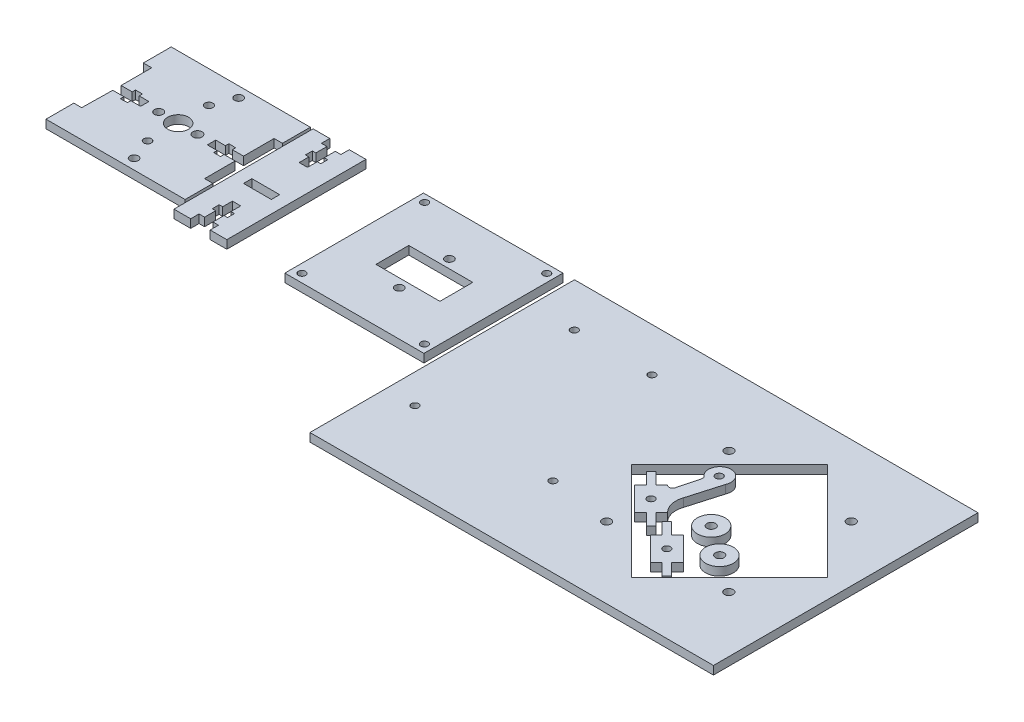
SolidWorks part; units mm, degrees
ref_plane "Front Plane" through (0, 0, 0) normal (0, 0, 1) x (1, 0, 0)
ref_plane "Top Plane" through (0, 0, 0) normal (0, 1, 0) x (1, 0, 0)
ref_plane "Right Plane" through (0, 0, 0) normal (1, 0, 0) x (0, 0, -1)
other "Graphic1"
other "Graphic (Closed) -1"
other "Graphic (Closed) -2"
other "Graphic (Closed) -3"
other "Graphic (Closed) -4"
other "Graphic (Closed) -5"
other "Graphic (Closed) -6"
other "Graphic (Closed) -7"
other "Graphic (Closed) -8"
other "Graphic (Closed) -9"
other "Graphic (Closed) -10"
other "Graphic (Closed) -11"
other "Graphic (Closed) -12"
other "Graphic (Closed) -13"
other "Graphic (Closed) -14"
other "Graphic (Closed) -15"
other "Graphic (Closed) -16"
other "Graphic (Closed) -17"
other "Graphic (Closed) -18"
other "Graphic (Closed) -19"
other "Graphic (Closed) -20"
other "Graphic (Closed) -21"
other "Graphic (Closed) -22"
other "Graphic (Closed) -23"
other "Graphic (Closed) -24"
other "Graphic (Closed) -25"
other "Graphic (Closed) -26"
other "Graphic (Closed) -27"
other "Graphic (Closed) -28"
other "Graphic (Closed) -29"
other "Graphic (Closed) -30"
other "Graphic (Closed) -31"
other "Graphic (Closed) -32"
other "Graphic (Closed) -33"
other "Graphic (Closed) -34"
other "Graphic (Closed) -35"
other "Graphic (Closed) -36"
other "Graphic (Closed) -37"
sketch "Sketch3" plane through (0, 0, 0) normal (0, 1, 0) x (1, 0, 0)
  line L0 (0, 0) -> (50, 0)
  line L1 (50, 0) -> (50, -10)
  line L2 (50, -10) -> (47, -10)
  line L3 (47, -10) -> (47, -21)
  line L4 (47, -21) -> (43, -21)
  line L5 (43, -21) -> (43, -19.8259)
  line L6 (43, -19.8259) -> (40.5, -19.75)
  line L7 (40.5, -19.75) -> (40.5, -21)
  line L8 (40.5, -21) -> (37, -21)
  line L9 (37, -21) -> (37, -24)
  line L10 (37, -24) -> (40.5, -24)
  line L11 (40.5, -24) -> (40.5, -25.275)
  line L12 (40.5, -25.275) -> (43, -25.25)
  line L13 (43, -25.25) -> (43, -24)
  line L14 (43, -24) -> (47, -24)
  line L15 (47, -24) -> (47, -35)
  line L16 (47, -35) -> (50, -35)
  line L17 (50, -35) -> (50, -45)
  line L18 (50, -45) -> (0, -45)
  line L19 (0, -45) -> (0, -35)
  line L20 (0, -35) -> (2.8271, -35)
  line L21 (3, -24) -> (7, -24)
  line L22 (7, -24) -> (7, -25.275)
  line L23 (7, -25.275) -> (9.5, -25.1741)
  line L24 (9.5, -25.1741) -> (9.5, -24)
  line L25 (9.5, -24) -> (13, -24)
  line L26 (13, -24) -> (13, -21)
  line L27 (13, -21) -> (9.5, -21)
  line L28 (9.5, -21) -> (9.5, -19.8259)
  line L29 (9.5, -19.8259) -> (7, -19.8259)
  line L30 (7, -19.8259) -> (7, -21)
  line L31 (7, -21) -> (3, -21)
  line L32 (3, -21) -> (3, -10)
  line L33 (3, -10) -> (0, -10)
  line L34 (0, -10) -> (0, 0)
  line L35 (2.8271, -35) -> (3, -24)
  circle A0 centre (25, -22.5) radius 3.75
  circle A1 centre (18, -22.5) radius 1.5333
  circle A2 centre (24.9904, -11.4176) radius 1.4239
  circle A3 centre (31.9506, -22.5119) radius 1.6482
  circle A4 centre (28, -3.75) radius 1.5
  circle A5 centre (25, -33.4941) radius 1.3524
  circle A6 centre (27.9864, -41.3394) radius 1.4891
  dimension "D1" = 10
extrude "Boss-Extrude1" add sketch "Sketch3" along normal blind 3
sketch "Sketch5" plane through (0, 0, 0) normal (0, 1, 0) x (1, 0, 0)
  line L0 (57, 0) -> (57, -3)
  line L1 (57, -3) -> (59, -3)
  line L2 (59, -3) -> (59, -7)
  line L3 (59, -7) -> (57.75, -7)
  line L4 (57.75, -7) -> (57.75, -9.5)
  line L5 (57.75, -9.5) -> (59, -9.5)
  line L6 (59, -9.5) -> (59, -13)
  line L7 (59, -13) -> (62, -13)
  line L8 (62, -13) -> (62, -9.5)
  line L9 (62, -9.5) -> (63.25, -9.5)
  line L10 (63.25, -9.5) -> (63.25, -7)
  line L11 (63.25, -7) -> (62, -7)
  line L12 (62, -7) -> (62, -3)
  line L13 (62, -3) -> (64, -3)
  line L14 (64, -3) -> (64, 0)
  line L15 (64, 0) -> (70, 0)
  line L16 (70, 0) -> (70, -50)
  line L17 (70, -50) -> (64, -50)
  line L18 (64, -50) -> (64, -47)
  line L19 (64, -47) -> (62, -47)
  line L20 (62, -47) -> (62, -43)
  line L21 (62, -43) -> (63.25, -43)
  line L22 (63.25, -43) -> (63.25, -40.5)
  line L23 (63.25, -40.5) -> (62, -40.5)
  line L24 (62, -40.5) -> (62, -37)
  line L25 (62, -37) -> (59, -37)
  line L26 (59, -37) -> (59, -40.5)
  line L27 (59, -40.5) -> (57.75, -40.5)
  line L28 (57.75, -40.5) -> (57.75, -43)
  line L29 (57.75, -43) -> (59, -43)
  line L30 (59, -43) -> (59, -47)
  line L31 (59, -47) -> (57, -47)
  line L32 (57, -47) -> (57, -50)
  line L33 (57, -50) -> (51, -50)
  line L34 (51, -50) -> (51, 0)
  line L35 (51, 0) -> (57, 0)
  line L36 (55.5, -26.5) -> (65.5, -26.5)
  line L37 (65.5, -26.5) -> (65.5, -29.5)
  line L38 (65.5, -29.5) -> (55.5, -29.5)
  line L39 (55.5, -29.5) -> (55.5, -26.5)
extrude "Boss-Extrude2" add sketch "Sketch5" along normal blind 3 separate body
sketch "Sketch8" plane through (0, 0, 0) normal (0, 1, 0) x (1, 0, 0)
  line L0 (104.5, -19.1) -> (127.5, -19.1)
  line L1 (127.5, -19.1) -> (127.5, -30.9)
  line L2 (127.5, -30.9) -> (104.5, -30.9)
  line L3 (104.5, -30.9) -> (104.5, -19.1)
  line L4 (90.8358, -0.1468) -> (90.8358, -49.9799)
  line L5 (90.8358, -49.9799) -> (140.8298, -49.9799)
  line L6 (140.8298, -49.9799) -> (140.8298, 0)
  line L7 (140.8298, 0) -> (90.8358, -0.1468)
  circle A0 centre (116, -16) radius 1.5
  circle A1 centre (116, -34) radius 1.5
  circle A2 centre (138, -3) radius 1.3
  circle A3 centre (94, -47) radius 1.3
  circle A4 centre (93.9724, -2.8702) radius 1.295
  circle A5 centre (138, -47) radius 1.3
extrude "Boss-Extrude3" add sketch "Sketch8" along normal blind 3 separate body
sketch "Sketch14" plane through (0, 0, 0) normal (0, 1, 0) x (1, 0, 0)
  line L0 (234.1407, -55.7028) -> (232.0194, -57.8241)
  line L1 (232.0194, -57.8241) -> (236.262, -62.0667)
  line L2 (236.262, -62.0667) -> (234.565, -63.7638)
  line L3 (234.565, -63.7638) -> (230.3223, -59.5211)
  line L4 (230.3223, -59.5211) -> (228.201, -61.6425)
  line L5 (228.201, -61.6425) -> (219.7157, -53.1572)
  line L6 (219.7157, -53.1572) -> (221.837, -51.0359)
  line L7 (221.837, -51.0359) -> (217.5944, -46.7932)
  line L8 (217.5944, -46.7932) -> (219.2915, -45.0962)
  line L9 (219.2915, -45.0962) -> (223.5341, -49.3388)
  line L10 (223.5341, -49.3388) -> (225.6554, -47.2175)
  line L11 (227.9135, -46.2821) -> (229.7551, -39.4354)
  line L12 (232.4436, -48.2782) -> (235.8289, -36.5593)
  line L14 (229.7551, -39.4354) -> (229.7551, -38.1986)
  line L15 (244.0402, -59.9454) -> (252.5255, -68.4307)
  line L16 (252.5255, -68.4307) -> (250.4042, -70.552)
  line L17 (250.4042, -70.552) -> (254.6468, -74.7947)
  line L18 (254.6468, -74.7947) -> (252.9497, -76.4917)
  line L19 (252.9497, -76.4917) -> (248.7071, -72.2491)
  line L20 (248.7071, -72.2491) -> (246.5858, -74.3704)
  line L21 (246.5858, -74.3704) -> (238.1005, -65.8851)
  line L22 (238.1005, -65.8851) -> (240.2218, -63.7638)
  line L23 (240.2218, -63.7638) -> (235.9792, -59.5211)
  line L24 (235.9792, -59.5211) -> (237.6762, -57.8241)
  line L25 (237.6762, -57.8241) -> (241.9189, -62.0667)
  line L26 (241.9189, -62.0667) -> (244.0402, -59.9454)
  arc A0 (225.6554, -47.2175) -> (227.9135, -46.2821) centre (226.5908, -46.2821) ccw
  arc A3 (234.1407, -55.7028) -> (232.4436, -48.2782) centre (239.2043, -50.6391) cw
  circle A4 centre (232.1046, -35.1115) radius 1.3
  arc A5 (235.8289, -36.5593) -> (229.7551, -38.1986) centre (232.1294, -34.9238) ccw
  circle A6 centre (226.9282, -54.43) radius 1.3
  circle A7 centre (246.1553, -52.0356) radius 1.55
  circle A8 centre (246.1553, -52.0356) radius 5
  circle A9 centre (256.8229, -59.6467) radius 1.55
  circle A10 centre (256.7818, -59.6877) radius 5.004
  circle A11 centre (245.313, -67.1579) radius 1.3
extrude "Boss-Extrude5" add sketch "Sketch14" along normal blind 3 separate body
sketch "Sketch10" plane through (0, 0, 0) normal (0, 1, 0) x (1, 0, 0)
  line L0 (144.971, 0) -> (144.971, -95.0975)
  line L1 (144.971, -95.0975) -> (290.0153, -95.0975)
  line L2 (290.0153, -95.0975) -> (290.0153, 0)
  line L3 (290.0153, 0) -> (144.971, 0)
  line L4 (247.9887, -12.0958) -> (283.1982, -47.3054)
  line L5 (283.1982, -47.3054) -> (247.9887, -82.5149)
  line L6 (247.9887, -82.5149) -> (212.7792, -47.3054)
  line L7 (212.7792, -47.3054) -> (247.9887, -12.0958)
  circle A0 centre (226, -25.5) radius 1.55
  circle A1 centre (188.5, -15.7) radius 1.3
  circle A2 centre (160.6, -15.7) radius 1.3
  circle A3 centre (155.5, -67.875) radius 1.2905
  circle A4 centre (203.7, -66.5) radius 1.3
  circle A5 centre (226, -69.5) radius 1.55
  circle A7 centre (269.94, -25.4918) radius 1.5641
  circle A8 centre (269.9229, -69.4833) radius 1.5564
extrude "Boss-Extrude4" add sketch "Sketch10" along normal blind 3 separate body
